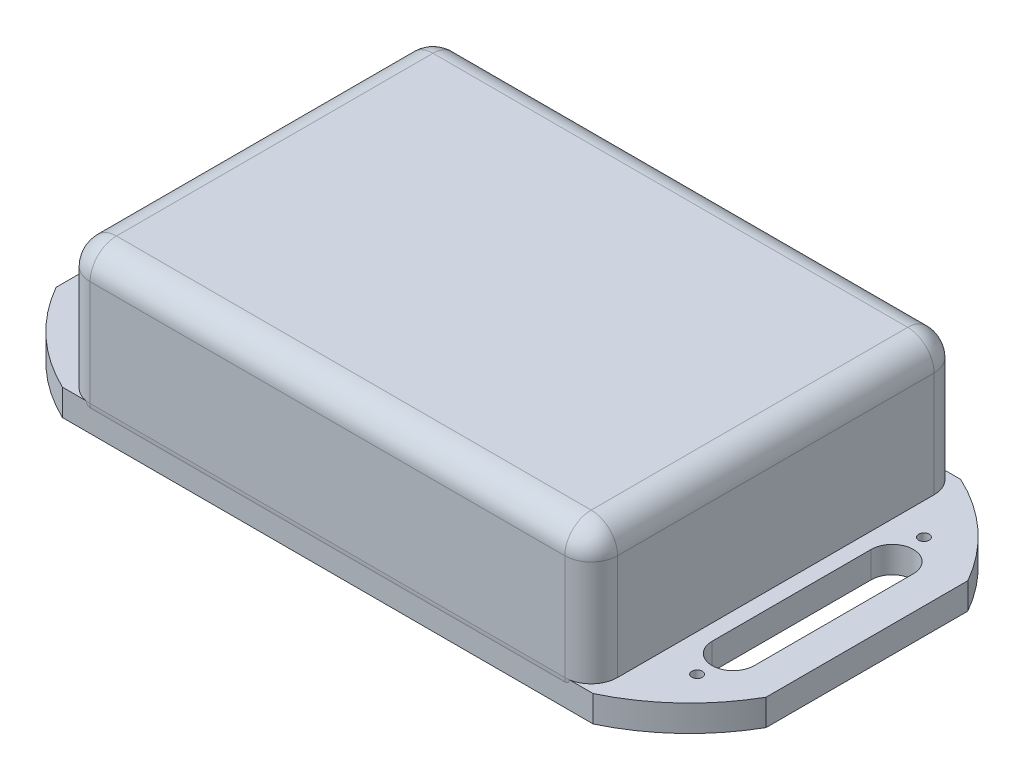
SolidWorks part; units mm, degrees
ref_plane "Front Plane" through (0, 0, 0) normal (0, 0, 1) x (1, 0, 0)
ref_plane "Top Plane" through (0, 0, 0) normal (0, 1, 0) x (1, 0, 0)
ref_plane "Right Plane" through (0, 0, 0) normal (1, 0, 0) x (0, 0, -1)
other "Center of Mass"
sketch "Sketch1" plane through (0, 0, 0) normal (0, 1, 0) x (1, 0, 0)
  line L0 (23.3839, 15.8839) -> (-23.3839, -15.8839) construction
  line L1 (-23.3839, 16.6161) -> (21.6161, 16.6161)
  line L2 (-25.8839, 14.1161) -> (-25.8839, -15.8839)
  line L3 (-23.3839, -18.3839) -> (21.6161, -18.3839)
  line L4 (24.1161, 14.1161) -> (24.1161, -15.8839)
  arc A0 (-23.3839, 16.6161) -> (-25.8839, 14.1161) centre (-23.3839, 14.1161) ccw
  arc A1 (21.6161, 16.6161) -> (24.1161, 14.1161) centre (21.6161, 14.1161) cw
  arc A2 (21.6161, -18.3839) -> (24.1161, -15.8839) centre (21.6161, -15.8839) ccw
  arc A3 (-25.8839, -15.8839) -> (-23.3839, -18.3839) centre (-23.3839, -15.8839) ccw
  point P6 (-25.8839, 16.6161)
  point P9 (24.1161, 16.6161)
  point P14 (-25.8839, -18.3839)
  point P16 (0, 0)
  dimension "D3" = 2.5
  dimension "D4" = 2.5
  dimension "D5" = 2.5
  dimension "D6" = 2.5
  dimension "D1" = 50
  dimension "D2" = 35
extrude "Boss-Extrude2" add sketch "Sketch1" along normal blind 15
fillet "Fillet2" radius 2.5 16 edges at (-25.8839, 0, 0.8839) (-25.1517, 0, 17.6517) (-0.8839, 0, 18.3839) (23.3839, 0, 17.6517) (24.1161, 0, 0.8839) (23.3839, 0, -15.8839) (-0.8839, 0, -16.6161) (-25.1517, 0, -15.8839) (-0.8839, 15, -16.6161) (23.3839, 15, -15.8839) (24.1161, 15, 0.8839) (23.3839, 15, 17.6517) (-0.8839, 15, 18.3839) (-25.1517, 15, 17.6517) (-25.8839, 15, 0.8839) (-25.1517, 15, -15.8839)
sketch "Sketch3" plane through (0, 0, 0) normal (0, 1, 0) x (1, 0, 0)
  line L0 (21.6161, 14.1161) -> (-23.3839, 14.1161) construction
  line L1 (-0.8839, 14.1161) -> (-0.8839, -15.8839)
  line L2 (-25.8839, 16.6469) -> (24.1161, 16.6469)
  line L3 (-34.5339, 8.6743) -> (-34.5339, -10.4535)
  line L4 (-26.039, -18.3531) -> (24.2713, -18.3531)
  line L6 (29.6161, 6.6585) -> (29.6161, -8.4263)
  line L7 (25.6161, 6.6585) -> (25.6161, -8.4263)
  line L8 (32.7661, 8.6743) -> (32.7661, -10.4535)
  line L9 (-23.3839, -15.8839) -> (21.6161, -15.8839) construction
  line L10 (32.7661, 8.6743) -> (32.7661, -10.4535)
  line L14 (-31.3839, 6.6585) -> (-31.3839, -8.4263)
  line L16 (-27.3839, 6.6585) -> (-27.3839, -8.4263)
  circle A0 centre (-28.8839, 10.1585) radius 0.5
  circle A1 centre (-29.3839, -11.8415) radius 0.5
  circle A2 centre (27.6161, -11.8415) radius 0.5
  circle A3 centre (27.1161, 10.1585) radius 0.5
  arc A4 (-27.3839, 6.6585) -> (-31.3839, 6.6585) centre (-29.3839, 6.6585) ccw
  arc A5 (-27.3839, -8.4263) -> (-31.3839, -8.4263) centre (-29.3839, -8.4263) cw
  arc A6 (25.6161, -8.4263) -> (29.6161, -8.4263) centre (27.6161, -8.4263) ccw
  arc A7 (25.6161, 6.6585) -> (29.6161, 6.6585) centre (27.6161, 6.6585) cw
  arc A8 (32.7661, -10.4535) -> (24.2713, -18.3531) centre (15.952, -0.8896) cw
  arc A9 (-34.5339, -10.4535) -> (-26.039, -18.3531) centre (-17.7198, -0.8896) ccw
  arc A10 (-25.8839, 16.6469) -> (-34.5339, 8.6743) centre (-17.7198, -0.8896) ccw
  arc A11 (24.1161, 16.6469) -> (32.7661, 8.6743) centre (15.952, -0.8896) cw
  dimension "D5" = 35
  dimension "D1" = 67.3
  dimension "D2" = 22
  dimension "D3" = 56
  dimension "D4" = 50
extrude "Boss-Extrude4" add sketch "Sketch3" along normal blind 2.5
other "Center of Mass Reference Point2"
